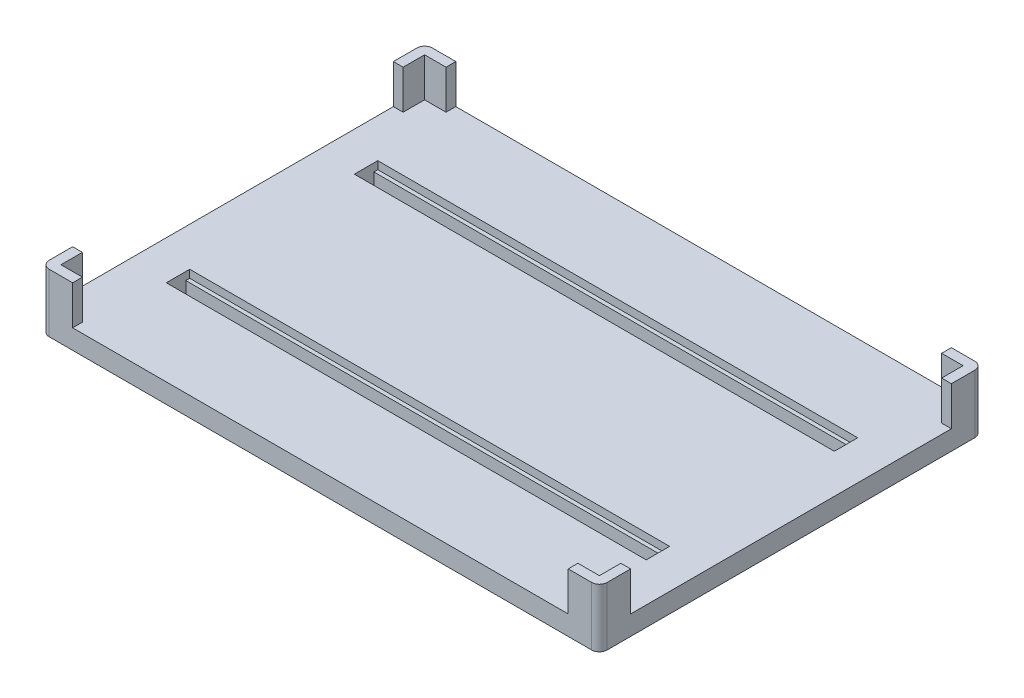
SolidWorks part; units mm, degrees
ref_plane "Front Plane" through (0, 0, 0) normal (0, 0, 1) x (1, 0, 0)
ref_plane "Top Plane" through (0, 0, 0) normal (0, 1, 0) x (1, 0, 0)
ref_plane "Right Plane" through (0, 0, 0) normal (1, 0, 0) x (0, 0, -1)
sketch "Sketch1" plane through (0, 0, 0) normal (0, 1, 0) x (1, 0, 0)
  line L1 (-69.5, -49.1) -> (69.5, -49.1)
  line L2 (-71.5, -47.1) -> (-71.5, 47.1)
  line L3 (-69.5, 49.1) -> (69.5, 49.1)
  line L4 (71.5, -47.1) -> (71.5, 47.1)
  line L5 (-71.5, -49.1) -> (71.5, 49.1) construction
  line L6 (-71.5, 49.1) -> (71.5, -49.1) construction
  arc A0 (69.5, -49.1) -> (71.5, -47.1) centre (69.5, -47.1) ccw
  arc A1 (-69.5, -49.1) -> (-71.5, -47.1) centre (-69.5, -47.1) cw
  arc A2 (69.5, 49.1) -> (71.5, 47.1) centre (69.5, 47.1) cw
  arc A3 (-71.5, 47.1) -> (-69.5, 49.1) centre (-69.5, 47.1) cw
  point P0 (0, 0)
  dimension "D3" = 2
  dimension "D1" = 143
  dimension "D2" = 98.2
extrude "Boss-Extrude1" add sketch "Sketch1" along normal blind 15
sketch "Sketch2" plane through (0, 15, 0) normal (0, 1, 0) x (1, 0, 0)
  line L1 (-69, -46.6) -> (69, -46.6)
  line L2 (-69, -46.6) -> (-69, 46.6)
  line L3 (-69, 46.6) -> (69, 46.6)
  line L4 (69, -46.6) -> (69, 46.6)
  line L5 (-69, -46.6) -> (69, 46.6) construction
  line L6 (-69, 46.6) -> (69, -46.6) construction
  point P0 (0, 0)
  dimension "D1" = 138
  dimension "D2" = 93.2
extrude "Cut-Extrude1" cut sketch "Sketch2" against normal blind 10
sketch "Sketch3" plane through (0, 15, 0) normal (0, 1, 0) x (1, 0, 0)
  line L0 (0, 56.4331) -> (0, -61.1236) construction
  line L1 (-87.5079, 0) -> (105.3906, 0) construction
  line L2 (-71.5, 47.1) -> (-71.5, -47.1) construction
  line L3 (-71.5, 41.1) -> (-69, 41.1)
  line L4 (-71.5, 41.1) -> (-71.5, -41.1)
  line L5 (-71.5, -41.1) -> (-69, -41.1)
  line L6 (-69, 41.1) -> (-69, -41.1)
  line L7 (-69, 46.6) -> (-69, -46.6) construction
  line L8 (69.5, 49.1) -> (-69.5, 49.1) construction
  line L9 (-69.5, -49.1) -> (69.5, -49.1) construction
  line L10 (69, 46.6) -> (-69, 46.6) construction
  line L11 (-63.5, 49.1) -> (63.5, 49.1)
  line L12 (-63.5, 49.1) -> (-63.5, 46.6)
  line L13 (-63.5, 46.6) -> (63.5, 46.6)
  line L14 (63.5, 49.1) -> (63.5, 46.6)
  line L15 (71.5, -47.1) -> (71.5, 47.1) construction
  line L16 (71.5, -41.1) -> (69, -41.1)
  line L17 (69, 41.1) -> (69, -41.1)
  line L18 (71.5, 41.1) -> (69, 41.1)
  line L19 (71.5, 41.1) -> (71.5, -41.1)
  line L20 (-63.5, -46.6) -> (63.5, -46.6)
  line L21 (63.5, -49.1) -> (63.5, -46.6)
  line L22 (-63.5, -49.1) -> (63.5, -49.1)
  line L23 (-63.5, -49.1) -> (-63.5, -46.6)
  dimension "D1" = 8
  dimension "D2" = 8
  dimension "D3" = 8
  dimension "D4" = 8
extrude "Cut-Extrude2" cut sketch "Sketch3" against normal blind 10
sketch "Sketch7" plane through (0, 5, 0) normal (0, 1, 0) x (1, 0, 0)
  line L0 (-71.5, 24.1) -> (71.5, 24.1) construction
  line L1 (-71.5, 41.1) -> (-71.5, -41.1) construction
  line L2 (71.5, -41.1) -> (71.5, 41.1) construction
  line L3 (-71.5, -24.1) -> (71.5, -24.1) construction
  line L4 (63.5, 49.1) -> (-63.5, 49.1) construction
  line L5 (-63.5, -49.1) -> (63.5, -49.1) construction
  line L7 (-61.5, 21.1) -> (61.5, 21.1)
  line L8 (-61.5, 21.1) -> (-61.5, 27.1)
  line L9 (-61.5, 27.1) -> (61.5, 27.1)
  line L10 (61.5, 21.1) -> (61.5, 27.1)
  line L11 (-61.5, 21.1) -> (61.5, 27.1) construction
  line L12 (-61.5, 27.1) -> (61.5, 21.1) construction
  line L13 (-61.5, -27.1) -> (61.5, -27.1)
  line L14 (-61.5, -27.1) -> (-61.5, -21.1)
  line L15 (-61.5, -21.1) -> (61.5, -21.1)
  line L16 (61.5, -27.1) -> (61.5, -21.1)
  line L17 (-61.5, -27.1) -> (61.5, -21.1) construction
  line L18 (-61.5, -21.1) -> (61.5, -27.1) construction
  point P12 (0, 24.1)
  point P17 (0, -24.1)
  dimension "D1" = 25
  dimension "D2" = 25
  dimension "D3" = 6
  dimension "D4" = 123
  dimension "D5" = 6
  dimension "D6" = 123
extrude "Cut-Extrude6" cut sketch "Sketch7" against normal blind 2
sketch "Sketch8" plane through (0, 3, 0) normal (0, 1, 0) x (1, 0, 0)
  line L0 (-61.5, 24.1) -> (61.5, 24.1) construction
  line L1 (-61.5, 27.1) -> (-61.5, 21.1) construction
  line L2 (61.5, 21.1) -> (61.5, 27.1) construction
  line L3 (-61.5, -24.1) -> (61.5, -24.1) construction
  line L4 (-61.5, -21.1) -> (-61.5, -27.1) construction
  line L5 (61.5, -27.1) -> (61.5, -21.1) construction
  line L7 (-61.5, 22.1) -> (61.5, 22.1)
  line L8 (-61.5, 22.1) -> (-61.5, 26.1)
  line L9 (-61.5, 26.1) -> (61.5, 26.1)
  line L10 (61.5, 22.1) -> (61.5, 26.1)
  line L11 (-61.5, 22.1) -> (61.5, 26.1) construction
  line L12 (-61.5, 26.1) -> (61.5, 22.1) construction
  line L13 (-61.5, -26.1) -> (61.5, -26.1)
  line L14 (-61.5, -26.1) -> (-61.5, -22.1)
  line L15 (-61.5, -22.1) -> (61.5, -22.1)
  line L16 (61.5, -26.1) -> (61.5, -22.1)
  line L17 (-61.5, -26.1) -> (61.5, -22.1) construction
  line L18 (-61.5, -22.1) -> (61.5, -26.1) construction
  point P12 (0, 24.1)
  point P17 (0, -24.1)
  dimension "D1" = 4
  dimension "D2" = 4
extrude "Cut-Extrude7" cut sketch "Sketch8" against normal blind 3
